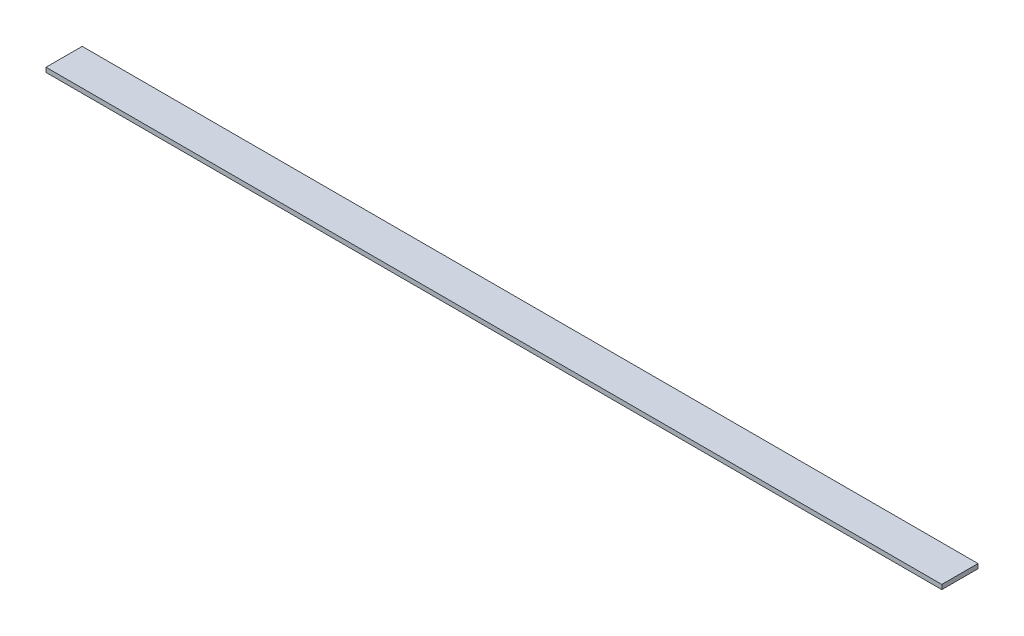
SolidWorks part; units mm, degrees
ref_plane "Front Plane" through (0, 0, 0) normal (0, 0, 1) x (1, 0, 0)
ref_plane "Top Plane" through (0, 0, 0) normal (0, 1, 0) x (1, 0, 0)
ref_plane "Right Plane" through (0, 0, 0) normal (1, 0, 0) x (0, 0, -1)
sketch "Sketch1" plane through (0, 0, 0) normal (0, 1, 0) x (1, 0, 0)
  line L2 (-628.65, 25.4) -> (628.65, 25.4)
  line L3 (-628.65, 25.4) -> (-628.65, -25.4)
  line L4 (-628.65, -25.4) -> (628.65, -25.4)
  line L5 (628.65, 25.4) -> (628.65, -25.4)
  line L6 (-628.65, 25.4) -> (628.65, -25.4) construction
  line L7 (-628.65, -25.4) -> (628.65, 25.4) construction
  point P1 (0, 0)
  dimension "D1" = 50.8
  dimension "D2" = 1257.3
extrude "Boss-Extrude1" add sketch "Sketch1" along normal blind 6.35
